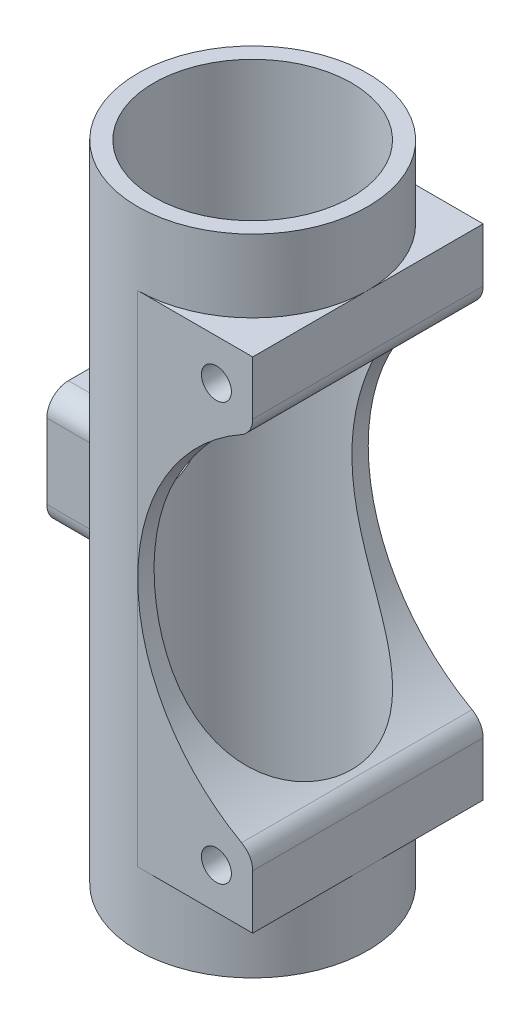
SolidWorks part; units mm, degrees
material "6061-T6 (SS)"
ref_plane "Front Plane" through (0, 0, 0) normal (0, 0, 1) x (1, 0, 0)
ref_plane "Top Plane" through (0, 0, 0) normal (0, 1, 0) x (1, 0, 0)
ref_plane "Right Plane" through (0, 0, 0) normal (1, 0, 0) x (0, 0, -1)
sketch "Sketch1" plane through (0, 0, 0) normal (0, 1, 0) x (1, 0, 0)
  circle A0 centre (0, 0) radius 10.9
  circle A1 centre (0, 0) radius 12.7
  dimension "D1" = 21.8
  dimension "D2" = 25.4
extrude "Boss-Extrude1" add sketch "Sketch1" along normal blind 71
sketch "Sketch2" plane through (0, 0, 0) normal (0, -1, 0) x (1, 0, 0)
  line L0 (0, 12.7) -> (12.7, 12.7)
  line L1 (12.7, 12.7) -> (12.7, -12.7)
  line L2 (12.7, -12.7) -> (0, -12.7)
  arc A0 (0, -12.7) -> (0, 12.7) centre (0, 0) ccw
  circle M1 centre (0, 0) radius 12.7
extrude "Boss-Extrude2" add sketch "Sketch2" against normal blind 63 contours L1 L0 M1 | L2 L1 M1
sketch "Sketch3" plane through (0, 0, 0) normal (0, -1, 0) x (1, 0, 0)
  line L0 (0, 12.7) -> (12.7, 12.7)
  line L1 (12.7, 12.7) -> (12.7, -12.7) construction
  line L2 (0, 12.7) -> (12.7, 12.7) construction
  line L3 (12.7, 12.7) -> (12.7, -12.7)
  line L4 (12.7, -12.7) -> (0, -12.7)
  arc A0 (0, -12.7) -> (0, 12.7) centre (0, 0) ccw
  line M2 (0, -12.7) -> (12.7, -12.7)
  line M3 (12.7, -12.7) -> (12.7, 12.7)
  line M4 (12.7, 12.7) -> (0, 12.7)
extrude "Cut-Extrude1" cut sketch "Sketch3" against normal blind 8 contours A0 L3 M4 | A0 M2 M3
sketch "Sketch4" plane through (0, 0, 0) normal (0, 0, 1) x (1, 0, 0)
  line L3 (12.7, 63) -> (12.7, 8) construction
  line L5 (10.4999, 35.5) -> (10.4999, 54.4) construction
  line L6 (10.4999, 35.5) -> (10.4999, 16.6) construction
  circle A3 centre (22.3312, 35.5) radius 22.2977
extrude "Cut-Extrude2" cut sketch "Sketch4" against normal blind 16 and the other way blind 15
sketch "Sketch5" plane through (0, 0, -12.7) normal (0, 0, -1) x (-1, 0, 0)
  line L0 (-12.7, 63) -> (-8.7, 63) construction
  line L1 (0, 63) -> (-12.7, 63) construction
  line L2 (-8.7, 63) -> (-8.7, 58.5) construction
  line L3 (-12.7, 8) -> (-8.7, 8) construction
  line L4 (-12.7, 8) -> (0, 8) construction
  line L5 (-8.7, 8) -> (-8.7, 12.5) construction
  circle A0 centre (-8.7, 58.5) radius 1.65
  circle A1 centre (-8.7, 12.5) radius 1.65
  dimension "D1" = 4.5
  dimension "D2" = 3.3
  dimension "D3" = 3.3
  dimension "D4" = 4.5
  dimension "D5" = 4
  dimension "D6" = 4
extrude "Cut-Extrude3" cut sketch "Sketch5" against normal blind 4
sketch "Sketch6" plane through (0, 0, 12.7) normal (0, 0, 1) x (1, 0, 0)
  line L0 (12.7, 63) -> (8.7, 63) construction
  line L1 (12.7, 63) -> (0, 63) construction
  line L2 (8.7, 63) -> (8.7, 58.5) construction
  line L3 (12.7, 8) -> (8.7, 8) construction
  line L4 (12.7, 8) -> (0, 8) construction
  line L5 (8.7, 8) -> (8.7, 12.5) construction
  circle A0 centre (8.7, 58.5) radius 1.65
  circle A1 centre (8.7, 12.5) radius 1.65
  dimension "D1" = 3.3
  dimension "D3" = 3.3
  dimension "D2" = 4.5
  dimension "D4" = 4.5
extrude "Cut-Extrude4" cut sketch "Sketch6" against normal blind 4
ref_plane "Plane1" through (0, 35.5, 0) normal (0, 1, 0) x (1, 0, 0)
sketch "Sketch14" plane through (0, 35.5, 0) normal (0, 1, 0) x (1, 0, 0)
  line L1 (-14.4365, -6.5) -> (-14.4365, 6.5)
  line L4 (-14.4365, 6.5) -> (-10.8366, 6.5)
  line L5 (-14.4365, -6.5) -> (-10.8366, -6.5)
  arc A1 (-10.8366, 6.5) -> (-10.8366, -6.5) centre (0, 0) ccw
  point P7 (-14.4365, 0)
extrude "Boss-Extrude3" add sketch "Sketch14" along normal blind 6.5 and the other way blind 6.5
sketch "Sketch15" plane through (-14.4365, 0, 0) normal (-1, 0, 0) x (0, 0, 1)
  line L0 (13.97, 35.5) -> (-13.97, 35.5) construction
  circle A0 centre (0, 35.5) radius 4
extrude "Cut-Extrude14" cut sketch "Sketch15" against normal blind 7.5
sketch "Sketch16" plane through (-14.4365, 0, 0) normal (-1, 0, 0) x (0, 0, 1)
  line L4 (6.5, 29) -> (6.5, 42)
  line L5 (6.5, 29) -> (6.5, 42)
  line L6 (-6.5, 42) -> (-6.5, 29)
  line L7 (-6.5, 42) -> (-6.5, 29)
  line L9 (6.5, 42) -> (-6.5, 42)
  line L11 (-6.5, 29) -> (6.5, 29)
  line L13 (6.5, 42) -> (-6.5, 42)
  line L15 (-6.5, 29) -> (6.5, 29)
  circle A2 centre (0, 35.5) radius 4
  circle A3 centre (0, 35.5) radius 4
  dimension "D1" = 0
  dimension "D2" = 0
extrude "Boss-Extrude4" add sketch "Sketch16" along normal blind 1.75
fillet "Fillet1" radius 2.38 4 edges at (-13.5485, 42, 6.5) (-13.5485, 29, 6.5) (-13.5485, 29, -6.5) (-13.5485, 42, -6.5)
fillet "Fillet2" radius 2.38 2 edges at (12.7, 55.6104, 0) (12.7, 15.3896, 0)
